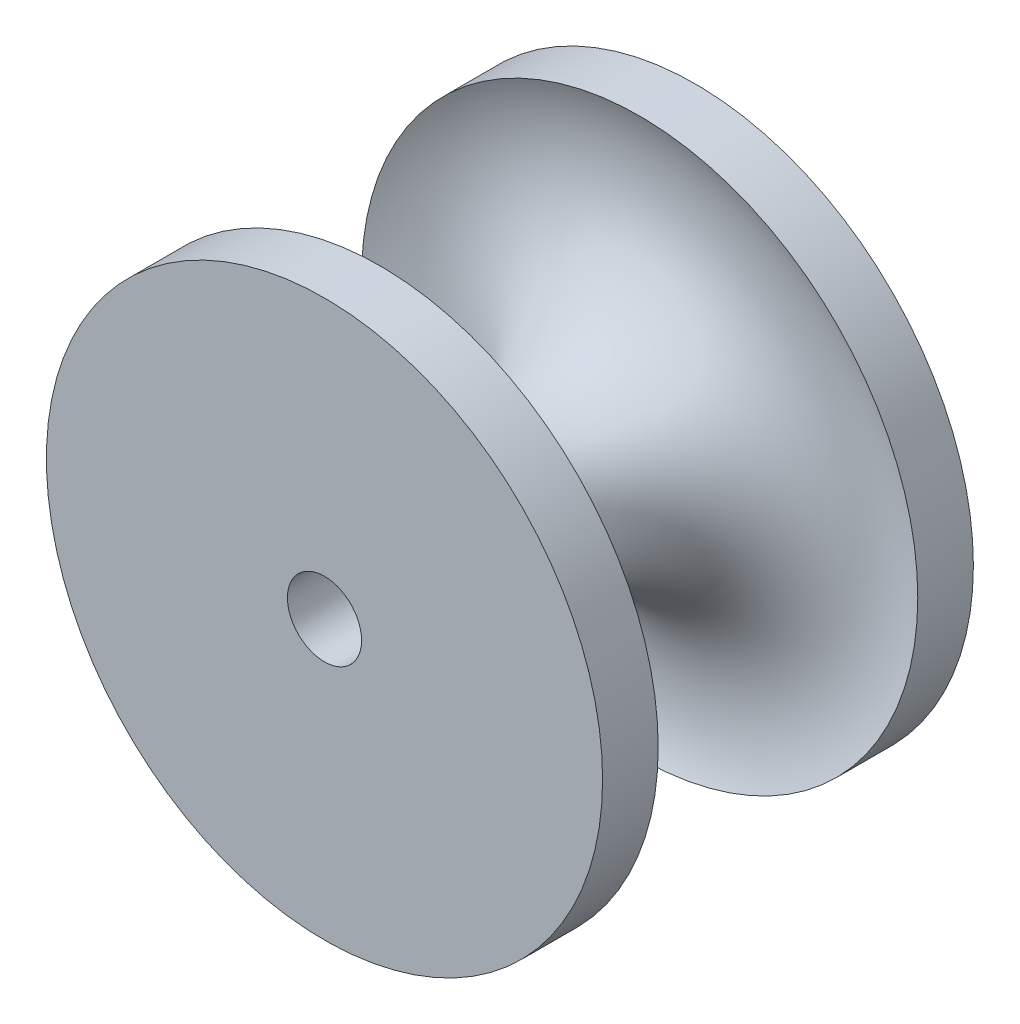
SolidWorks part; units mm, degrees
ref_plane "Front Plane" through (0, 0, 0) normal (0, 0, 1) x (1, 0, 0)
ref_plane "Top Plane" through (0, 0, 0) normal (0, 1, 0) x (1, 0, 0)
ref_plane "Right Plane" through (0, 0, 0) normal (1, 0, 0) x (0, 0, -1)
sketch "Sketch1" plane through (0, 0, 0) normal (0, 0, 1) x (1, 0, 0)
  circle A0 centre (0, 0) radius 19.05
extrude "Boss-Extrude1" add sketch "Sketch1" along normal blind 25.4 contours A0
sketch "Sketch2" plane through (0, 0, 0) normal (1, 0, 0) x (0, 0, -1)
  line L2 (-36.402, 0) -> (15.8289, 0) construction
  line L8 (0, 19.05) -> (-25.4, 19.05) construction
  line L12 (-3.81, 19.05) -> (-21.59, 19.05)
  arc A1 (-21.59, 19.05) -> (-3.81, 19.05) centre (-12.7, 14.9294) ccw
revolve "Cut-Revolve1" cut sketch "Sketch2" angle 360 about L2
sketch "Sketch3" plane through (0, 0, 0) normal (0, 0, 1) x (1, 0, 0)
  circle A1 centre (0, 0) radius 2.54
extrude "Cut-Extrude1" cut sketch "Sketch3" along normal blind 36.83 and the other way blind 7.366 contours A1
